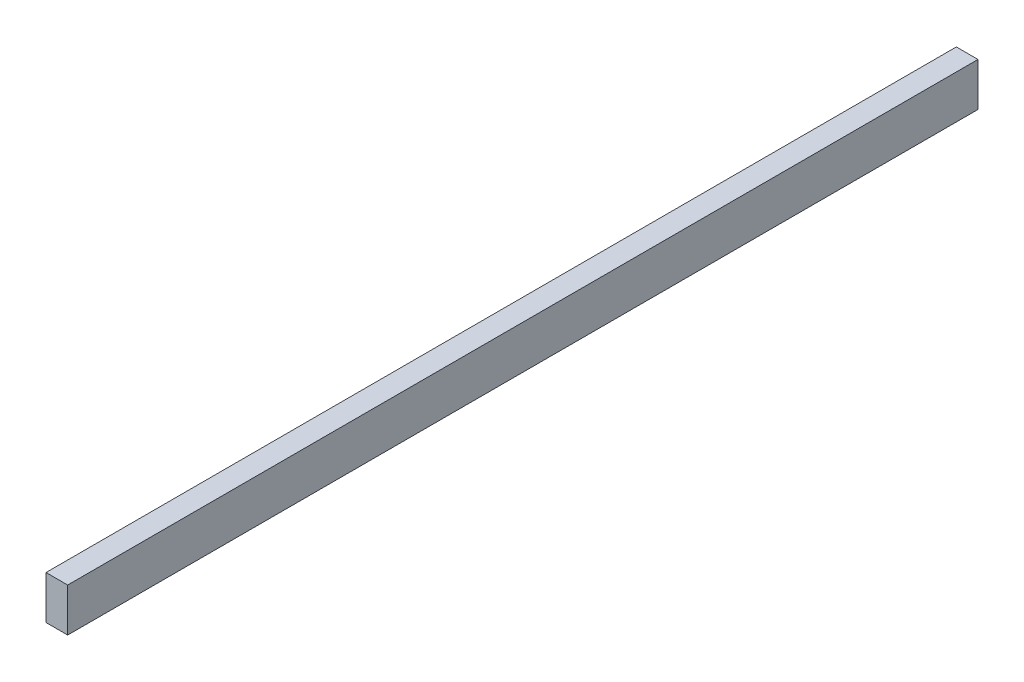
SolidWorks part; units mm, degrees
ref_plane "Front Plane" through (0, 0, 0) normal (0, 0, 1) x (1, 0, 0)
ref_plane "Top Plane" through (0, 0, 0) normal (0, 1, 0) x (1, 0, 0)
ref_plane "Right Plane" through (0, 0, 0) normal (1, 0, 0) x (0, 0, -1)
sketch "Sketch1" plane through (0, 0, 0) normal (0, 0, 1) x (1, 0, 0)
  line L1 (-25.4, -50.8) -> (25.4, -50.8)
  line L2 (-25.4, -50.8) -> (-25.4, 50.8)
  line L3 (-25.4, 50.8) -> (25.4, 50.8)
  line L4 (25.4, -50.8) -> (25.4, 50.8)
  line L5 (-25.4, -50.8) -> (25.4, 50.8) construction
  line L6 (-25.4, 50.8) -> (25.4, -50.8) construction
  point P0 (0, 0)
  dimension "D1" = 50.8
  dimension "D2" = 101.6
extrude "Boss-Extrude1" add sketch "Sketch1" along normal blind 2133.6
